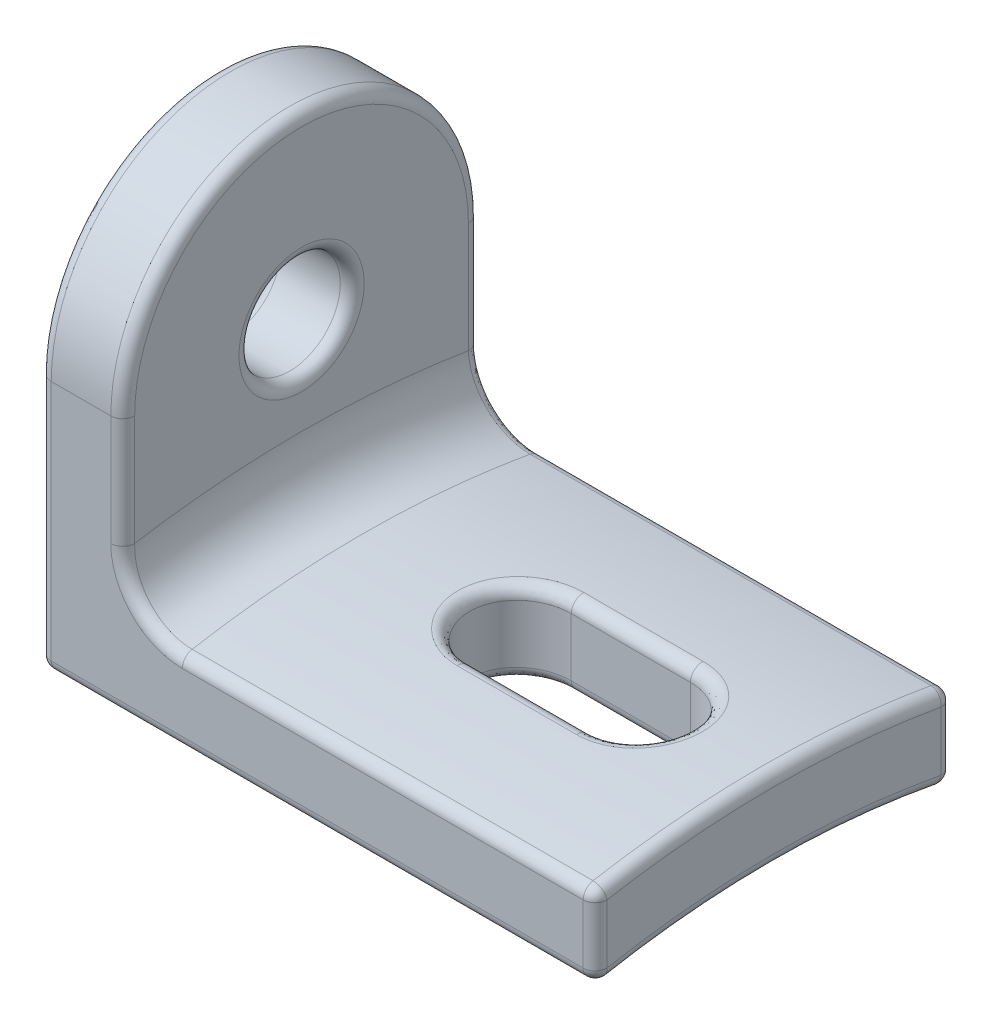
SolidWorks part; units mm, degrees
ref_plane "Front Plane" through (0, 0, 0) normal (0, 0, 1) x (1, 0, 0)
ref_plane "Top Plane" through (0, 0, 0) normal (0, 1, 0) x (1, 0, 0)
ref_plane "Right Plane" through (0, 0, 0) normal (1, 0, 0) x (0, 0, -1)
sketch "Sketch1" plane through (0, 0, 0) normal (1, 0, 0) x (0, 0, -1)
  line L0 (0, 0) -> (0, -8) construction
  line L1 (0, -8) -> (0, -38) construction
  line L2 (-6, 0) -> (-6, -8.6061)
  line L3 (6, 0) -> (6, -8.6061)
  circle A1 centre (0, 0) radius 1.7
  circle A2 centre (0, -38) radius 30
  circle A3 centre (0, 0) radius 6
  dimension "D1" = 3.4
  dimension "D3" = 60
  dimension "D4" = 12
  dimension "D2" = 8
extrude "Boss-Extrude1" add sketch "Sketch1" along normal blind 2.8 contours A3 A1 | A3 L2 A2 L3
sketch "Sketch2" plane through (0, 0, 0) normal (-1, 0, 0) x (0, 0, 1)
  line L0 (-6, -8.6061) -> (-6, -5.8061)
  line L1 (6, -8.6061) -> (6, -5.8061)
  line L2 (6, 0) -> (6, -8.6061) construction
  arc A0 (6, -8.6061) -> (-6, -8.6061) centre (0, -38) ccw construction
  arc A1 (6, -8.6061) -> (-6, -8.6061) centre (0, -38) ccw
  arc A2 (6, -5.8061) -> (-6, -5.8061) centre (0, -38) ccw
  dimension "D1" = 2.8
extrude "Boss-Extrude2" add sketch "Sketch2" against normal blind 18.65
sketch "Sketch3" plane through (0, 0, 0) normal (0, 1, 0) x (1, 0, 0)
  line L0 (14.15, 0) -> (10.15, 0) construction
  line L1 (14.15, -1.7) -> (10.15, -1.7)
  line L2 (14.15, 1.7) -> (10.15, 1.7)
  line L3 (15.85, 0) -> (18.65, 0) construction
  arc A0 (14.15, -1.7) -> (14.15, 1.7) centre (14.15, 0) ccw
  arc A1 (10.15, 1.7) -> (10.15, -1.7) centre (10.15, 0) ccw
  point P3 (12.15, 0)
  dimension "D1" = 1.7
  dimension "D2" = 12.15
  dimension "D3" = 4
  dimension "D4" = 2.8
extrude "Cut-Extrude1" cut sketch "Sketch3" against normal blind 15.5 contours A1 L1 A0 L2
fillet "Fillet1" radius 2 1 edges at (2.8, -5.2518, 0)
fillet "Fillet2" radius 0.4 27 edges at (0, -4.3031, 6) (0, 6, 0) (11.725, -5.8061, 6) (3.5663, -5.373, 6) (2.8, -1.8869, 6) (2.8, 6, 0) (12.15, -5.2959, -1.7) (15.8387, -5.2524, -0.1957) (12.15, -5.2959, 1.7) (12.15, -8.0482, 1.7) (15.8387, -8.0006, 0.1955) (12.15, -8.0482, -1.7) (0, -4.3031, -6) (9.325, -8.6061, -6) (11.725, -5.8061, -6) (3.2505, -5.0583, -6) (2.8, -1.8869, -6) (18.65, -7.2061, 6) (18.65, -5.2518, 0) (18.65, -7.2061, -6) (18.65, -8, 0) (0, 0, -1.7) (2.8, 0, -1.7) (8.4613, -5.2524, 0.1957) (8.4613, -8.0006, -0.1955) (0, -8, 0) (9.325, -8.6061, 6)
